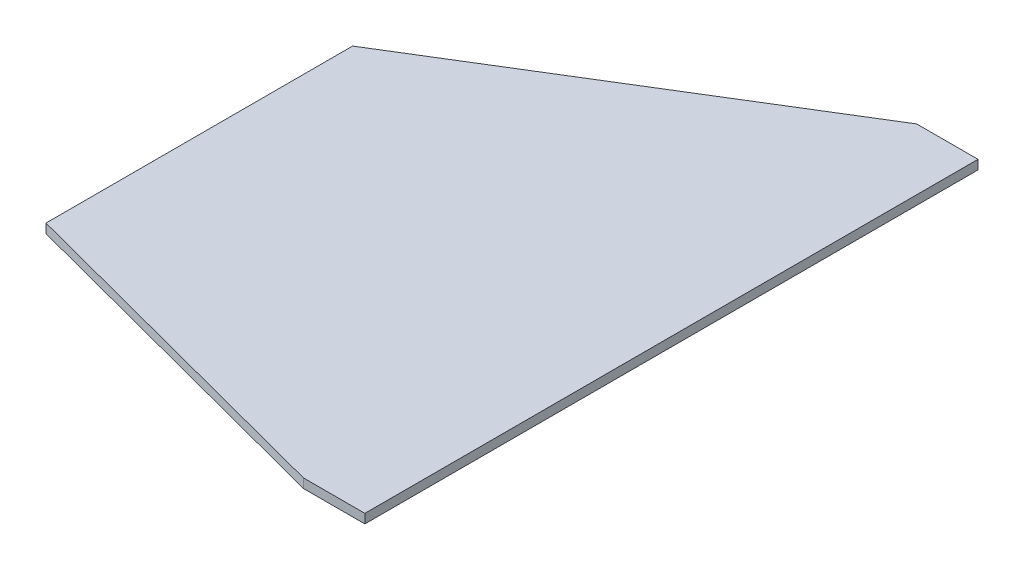
SolidWorks part; units mm, degrees
ref_plane "Front Plane" through (0, 0, 0) normal (0, 0, 1) x (1, 0, 0)
ref_plane "Top Plane" through (0, 0, 0) normal (0, 1, 0) x (1, 0, 0)
ref_plane "Right Plane" through (0, 0, 0) normal (1, 0, 0) x (0, 0, -1)
sketch "Sketch1" plane through (0, 0, 0) normal (0, 1, 0) x (1, 0, 0)
  line L0 (0, 0) -> (0, 100)
  line L1 (0, 100) -> (-57, 65)
  line L2 (-57, 65) -> (-57, 15)
  line L3 (-57, 15) -> (0, 0)
  line L4 (0, 100) -> (10, 100)
  line L5 (10, 100) -> (10, 0)
  line L6 (10, 0) -> (0, 0)
  dimension "D1" = 100
  dimension "D2" = 50
  dimension "D3" = 57
  dimension "D4" = 35
  dimension "D5" = 10
extrude "Boss-Extrude1" add sketch "Sketch1" along normal blind 1.5 contours L2 L3 L0 L1 | L6 L5 L4 L0
